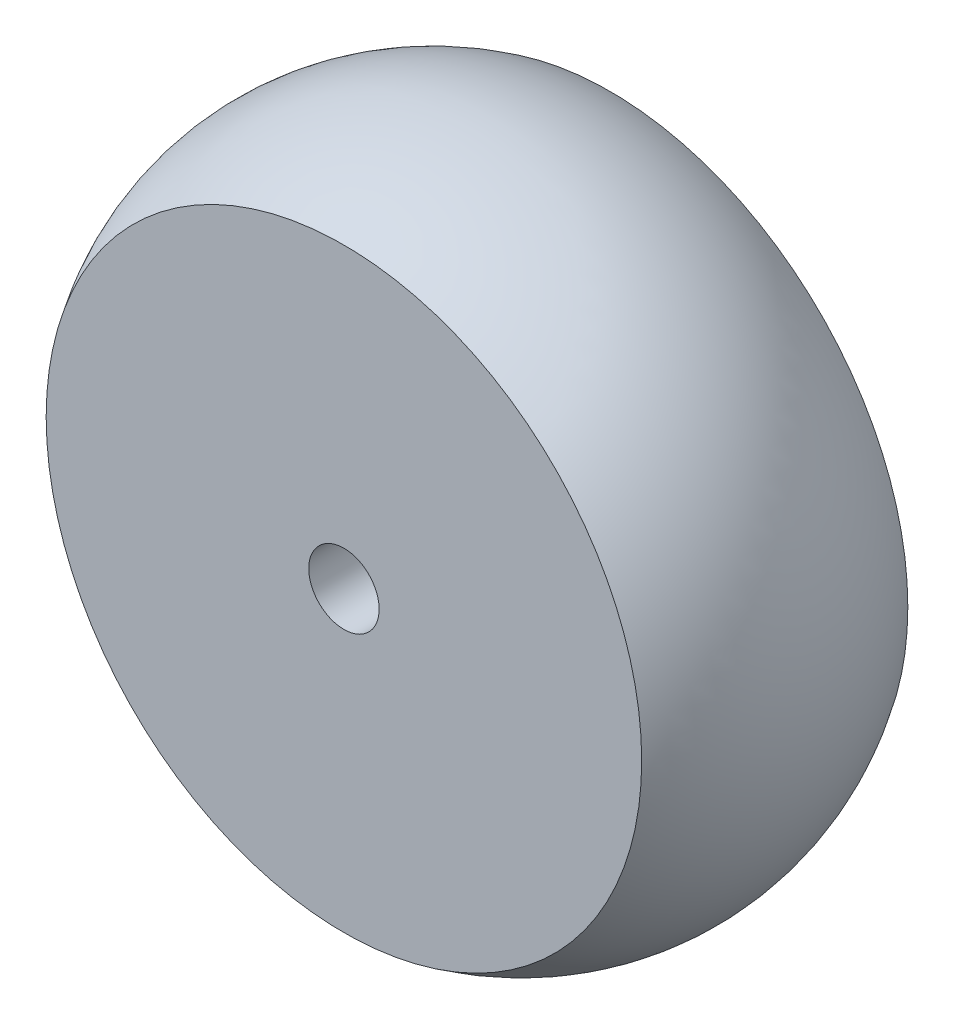
SolidWorks part; units mm, degrees
ref_plane "Front Plane" through (0, 0, 0) normal (0, 0, 1) x (1, 0, 0)
ref_plane "Top Plane" through (0, 0, 0) normal (0, 1, 0) x (1, 0, 0)
ref_plane "Right Plane" through (0, 0, 0) normal (1, 0, 0) x (0, 0, -1)
sketch "Sketch1" plane through (0, 0, 0) normal (1, 0, 0) x (0, 0, -1)
  line L1 (0, 0) -> (0, 20.8528) construction
  line L2 (0, 0) -> (33.2512, 0) construction
  line L3 (0, 1.5875) -> (0, 13.4268)
  line L4 (0, 1.5875) -> (12, 1.5875)
  line L5 (12, 1.5875) -> (12, 13.4268)
  line L6 (0, 13.4268) -> (12, 13.4268) construction
  line L7 (6, 13.4268) -> (6, 0) construction
  line L8 (6, 13.4268) -> (6, 20.8528) construction
  arc A0 (0, 13.4268) -> (12, 13.4268) centre (6, 4.4658) cw
  point P12 (6, 15.25)
  dimension "D1" = 15.25
  dimension "D2" = 12
  dimension "D3" = 1.5875
revolve "Revolve1" add sketch "Sketch1" angle 360 about L2
